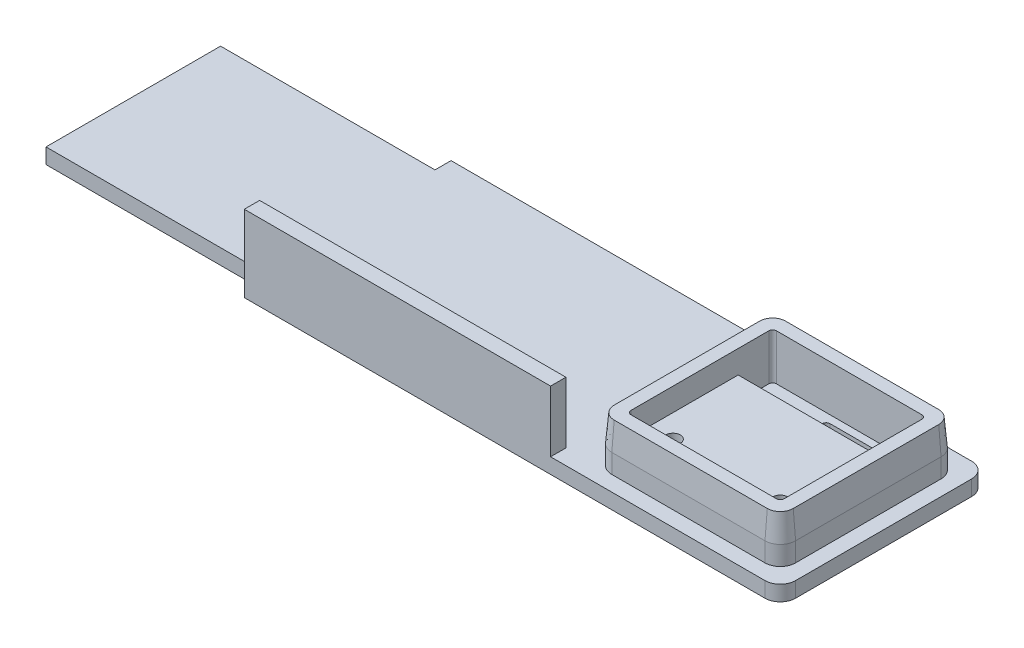
SolidWorks part; units mm, degrees
ref_plane "Front Plane" through (0, 0, 0) normal (0, 0, 1) x (1, 0, 0)
ref_plane "Top Plane" through (0, 0, 0) normal (0, 1, 0) x (1, 0, 0)
ref_plane "Right Plane" through (0, 0, 0) normal (1, 0, 0) x (0, 0, -1)
sketch "Sketch1" plane through (0, 0, 0) normal (0, 1, 0) x (1, 0, 0)
  line L1 (-14, -13.5) -> (14, -13.5)
  line L2 (-14, -13.5) -> (-14, 13.5)
  line L3 (-14, 13.5) -> (14, 13.5)
  line L4 (14, -13.5) -> (14, 13.5)
  line L5 (-14, -13.5) -> (14, 13.5) construction
  line L6 (-14, 13.5) -> (14, -13.5) construction
  point P0 (0, 0)
  dimension "D1" = 28
  dimension "D2" = 27
extrude "Boss-Extrude1" add sketch "Sketch1" along normal blind 2
sketch "Sketch2" plane through (0, 2, 0) normal (0, 1, 0) x (1, 0, 0)
  line L0 (14, 13.5) -> (-14, 13.5) construction
  line L1 (-2, 6) -> (8, 6)
  line L2 (-2, 6) -> (-2, 8.5)
  line L3 (-2, 8.5) -> (8, 8.5)
  line L4 (8, 6) -> (8, 8.5)
  line L5 (-2, 6) -> (8, 8.5) construction
  line L6 (-2, 8.5) -> (8, 6) construction
  line L7 (14, -13.5) -> (14, 13.5) construction
  point P0 (3, 7.25)
  dimension "D1" = 10
  dimension "D2" = 2.5
  dimension "D3" = 5
  dimension "D4" = 6
extrude "Cut-Extrude1" cut sketch "Sketch2" against normal up to surface (2 mm away) up to face at (0, 0, 0)
sketch "Sketch3" plane through (0, 2, 0) normal (0, 1, 0) x (1, 0, 0)
  line L0 (-10, -9.5) -> (10, -9.5)
  line L1 (10, -9.5) -> (10, 5)
  line L2 (10, 5) -> (-10, 5)
  line L3 (0, 13.5) -> (0, -13.5) construction
  line L4 (14, 13.5) -> (-14, 13.5) construction
  line L5 (-14, -13.5) -> (14, -13.5) construction
  line L6 (14, -13.5) -> (14, 13.5) construction
  line L7 (-2, 6) -> (8, 6) construction
  line L8 (-10, -9.5) -> (-10, 5)
  point P17 (0, -9.5)
  point P18 (0, 5)
  dimension "D1" = 4
  dimension "D2" = 4
  dimension "D3" = 1
extrude "Boss-Extrude2" add sketch "Sketch3" along normal blind 3
sketch "Sketch4" plane through (0, 2, 0) normal (0, 1, 0) x (1, 0, 0)
  line L0 (12, 11.5) -> (12, -11.5)
  line L1 (12, -11.5) -> (-12, -11.5)
  line L2 (-12, -11.5) -> (-12, 11.5)
  line L3 (-12, 11.5) -> (12, 11.5)
  line L4 (-10, -9.5) -> (-10, 9.5)
  line L5 (-10, 9.5) -> (10, 9.5)
  line L6 (10, 9.5) -> (10, -9.5)
  line L7 (10, -9.5) -> (-10, -9.5)
  line L8 (14, 13.5) -> (-14, 13.5) construction
  dimension "D1" = 2
  dimension "D2" = 2
  dimension "D3" = 2
  dimension "D4" = 2
  dimension "D5" = 2
extrude "Boss-Extrude3" add sketch "Sketch4" along normal blind 6
sketch "Sketch5" plane through (0, 5, 0) normal (0, 1, 0) x (1, 0, 0)
  line L0 (0, 5) -> (0, -9.5) construction
  line L1 (10, 5) -> (-10, 5) construction
  line L2 (-10, -9.5) -> (10, -9.5) construction
  circle A0 centre (-7, -6.5) radius 0.95
  circle A1 centre (7, -6.5) radius 0.95
  dimension "D3" = 1.9
  dimension "D1" = 7
  dimension "D2" = 3
extrude "Cut-Extrude2" cut sketch "Sketch5" against normal blind 3.2
fillet "Fillet3" radius 2 6 edges at (14, 1, -13.5) (14, 1, 13.5) (12, 5, -11.5) (12, 5, 11.5) (-12, 5, 11.5) (-12, 5, -11.5)
fillet "Fillet2" radius 0.5 8 edges at (-10, 6.5, 9.5) (10, 6.5, 9.5) (10, 5, -9.5) (-10, 5, -9.5) (-2, 1, -6) (-2, 1, -8.5) (8, 1, -8.5) (8, 1, -6)
sketch "Sketch6" plane through (-14, 0, 0) normal (-1, 0, 0) x (0, 0, 1)
  line L1 (-13.5, 0) -> (13.5, 0)
  line L2 (-13.5, 0) -> (-13.5, 2)
  line L3 (-13.5, 2) -> (13.5, 2)
  line L4 (13.5, 0) -> (13.5, 2)
extrude "Boss-Extrude4" add sketch "Sketch6" along normal blind 70
chamfer "Chamfer1" distance 3.5 angle 5 8 edges at (0, 8, -11.5) (-11.4142, 8, -10.9142) (11.4142, 8, -10.9142) (-12, 8, 0) (12, 8, 0) (-11.4142, 8, 10.9142) (11.4142, 8, 10.9142) (0, 8, 11.5)
sketch "Sketch7" plane through (0, 2, 0) normal (0, 1, 0) x (1, 0, 0)
  line L0 (-84, -13.5) -> (-84, 13.5) construction
  line L2 (12, 13.5) -> (-84, 13.5) construction
  line L3 (-84, 11.4) -> (-56, 11.4)
  line L4 (-84, 11.4) -> (-84, 13.5)
  line L5 (-84, 13.5) -> (-56, 13.5)
  line L6 (-56, 11.4) -> (-56, 13.5)
  dimension "D1" = 2.1
  dimension "D2" = 28
extrude "Cut-Extrude3" cut sketch "Sketch7" against normal through all
mirror "Mirror1" about plane through (0, 0, 0) normal (0, 0, 1) of "Cut-Extrude3"
sketch "Sketch8" plane through (0, 0, 13.5) normal (0, 0, 1) x (1, 0, 0)
  line L0 (-56, 2) -> (-16, 2)
  line L1 (-56, 2) -> (12, 2) construction
  line L2 (-16, 2) -> (-16, 10)
  line L3 (-16, 10) -> (-56, 10)
  line L4 (-56, 10) -> (-56, 2)
  line L5 (-12, 2) -> (-12, 4.5) construction
  dimension "D1" = 4
  dimension "D2" = 8
extrude "Boss-Extrude5" add sketch "Sketch8" against normal blind 2
